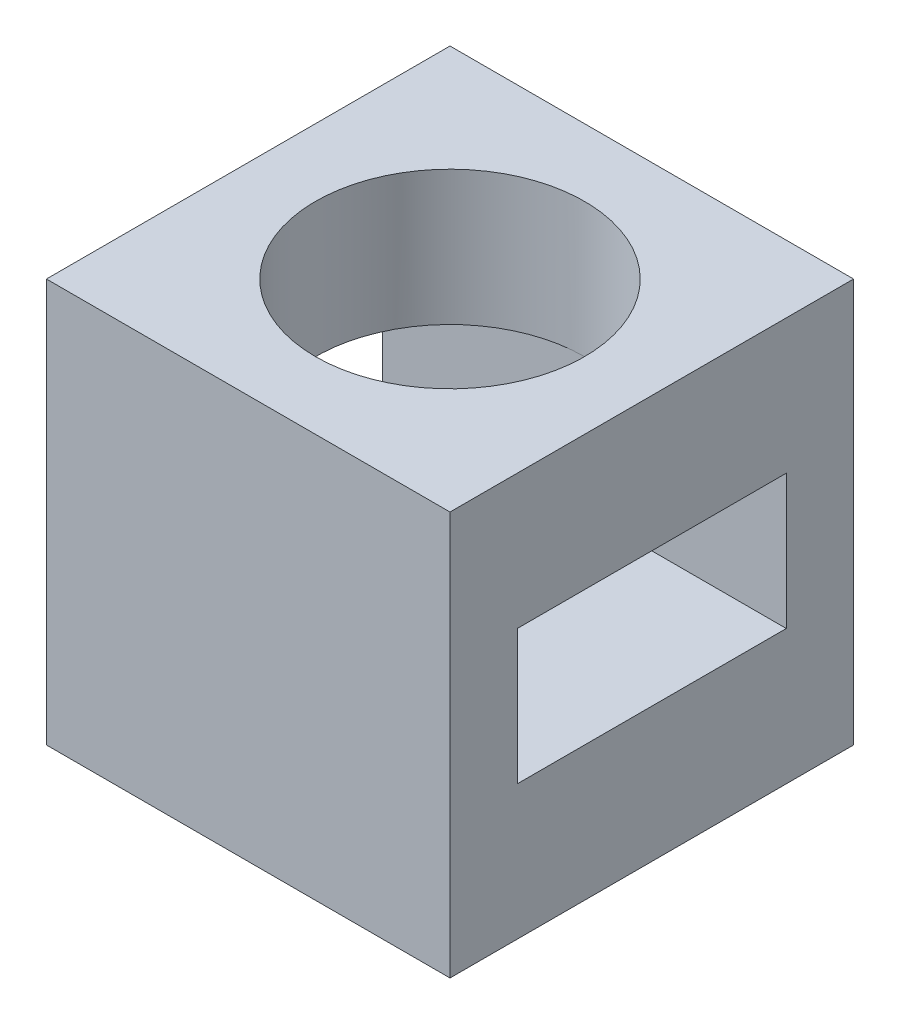
SolidWorks part; units mm, degrees
ref_plane "Front Plane" through (0, 0, 0) normal (0, 0, 1) x (1, 0, 0)
ref_plane "Top Plane" through (0, 0, 0) normal (0, 1, 0) x (1, 0, 0)
ref_plane "Right Plane" through (0, 0, 0) normal (1, 0, 0) x (0, 0, -1)
sketch "Sketch1" plane through (0, 0, 0) normal (1, 0, 0) x (0, 0, -1)
  line L1 (-75, 75) -> (75, 75)
  line L2 (-75, 75) -> (-75, -75)
  line L3 (-75, -75) -> (75, -75)
  line L4 (75, 75) -> (75, -75)
  line L5 (-75, 75) -> (75, -75) construction
  line L6 (-75, -75) -> (75, 75) construction
  line L7 (-50, 25) -> (50, 25)
  line L8 (-50, 25) -> (-50, -25)
  line L9 (-50, -25) -> (50, -25)
  line L10 (50, 25) -> (50, -25)
  line L11 (-50, 25) -> (50, -25) construction
  line L12 (-50, -25) -> (50, 25) construction
  point P0 (0, 0)
  point P6 (0, 0)
  dimension "D1" = 150
  dimension "D2" = 50
  dimension "D3" = 100
extrude "Boss-Extrude1" add sketch "Sketch1" along normal blind 150
sketch "Sketch3" plane through (0, 75, 0) normal (0, 1, 0) x (1, 0, 0)
  line L0 (0, 75) -> (150, -75) construction
  line L1 (0, -75) -> (150, 75) construction
  circle A0 centre (75, 0) radius 50
  dimension "D1" = 100
extrude "Cut-Extrude1" cut sketch "Sketch3" against normal blind 50
